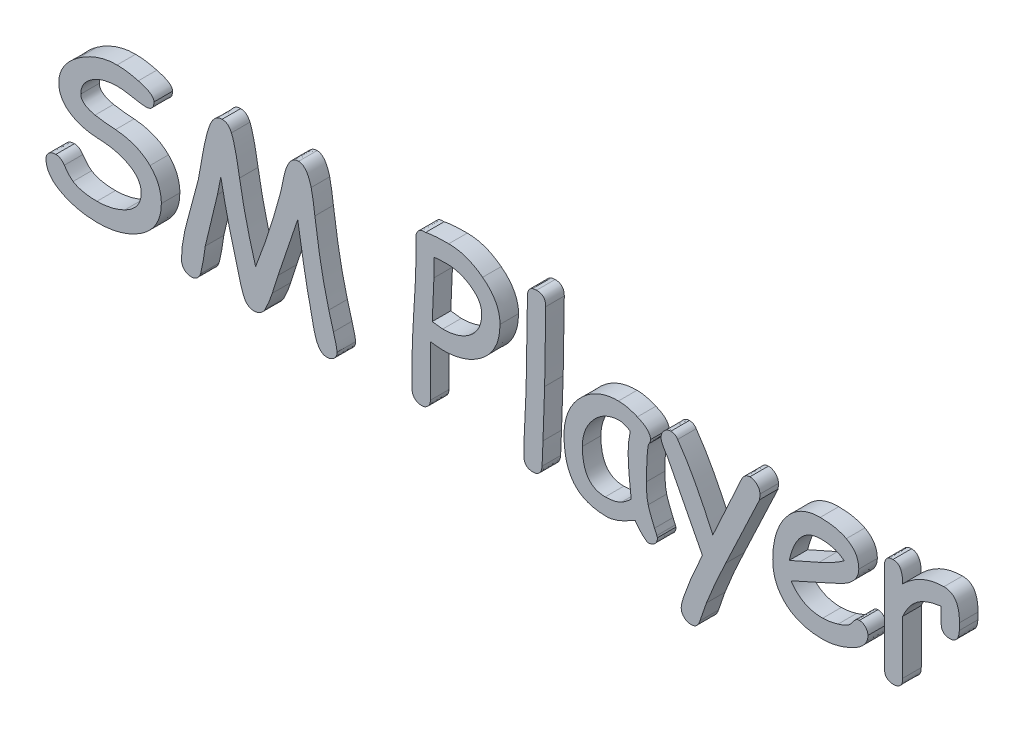
SolidWorks part; units mm, degrees
ref_plane "Front Plane" through (0, 0, 0) normal (0, 0, 1) x (1, 0, 0)
ref_plane "Top Plane" through (0, 0, 0) normal (0, 1, 0) x (1, 0, 0)
ref_plane "Right Plane" through (0, 0, 0) normal (1, 0, 0) x (0, 0, -1)
sketch "Sketch1" plane through (0, 0, 0) normal (0, 0, 1) x (1, 0, 0)
  text T0 "SM Player" font "Comic Sans MS" height in points 28
extrude "Boss-Extrude1" add sketch "Sketch1" along normal blind 1
